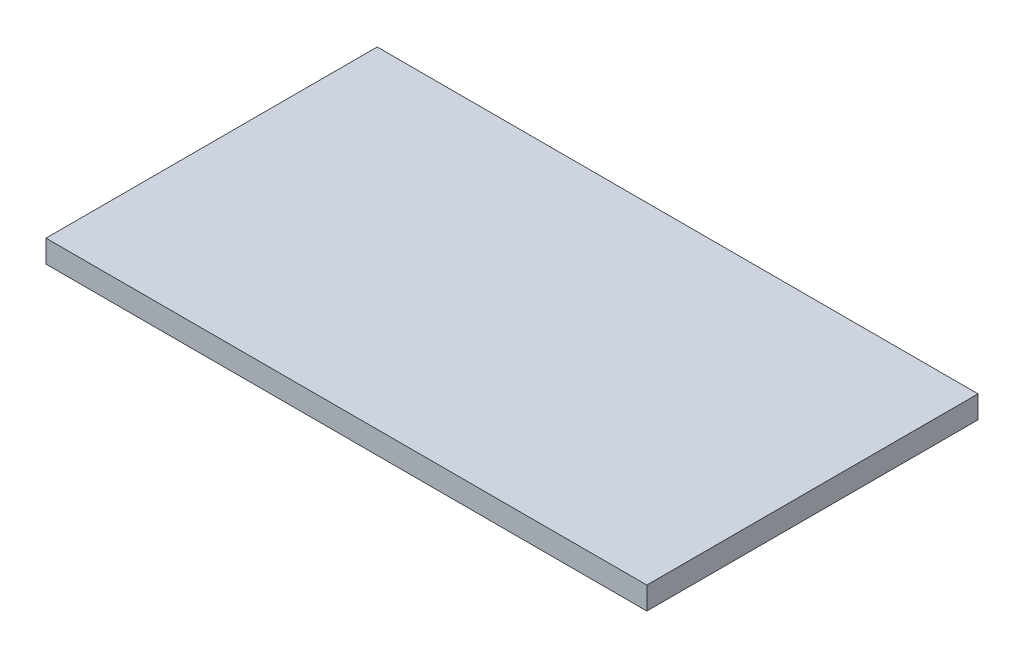
SolidWorks part; units mm, degrees
ref_plane "Alzado" through (0, 0, 0) normal (0, 0, 1) x (1, 0, 0)
ref_plane "Planta" through (0, 0, 0) normal (0, 1, 0) x (1, 0, 0)
ref_plane "Vista lateral" through (0, 0, 0) normal (1, 0, 0) x (0, 0, -1)
sketch "Croquis1" plane through (0, 0, 0) normal (0, 1, 0) x (1, 0, 0)
  line L0 (0, 0) -> (0, 140)
  line L1 (0, 140) -> (254, 140)
  line L2 (0, 0) -> (254, 0)
  line L5 (127, 51.93) -> (127, 140) construction
  line L6 (254, 140) -> (254, 0)
  dimension "D1" = 140
  dimension "D2" = 254
extrude "Saliente-Extruir1" add sketch "Croquis1" along normal blind 9.525
